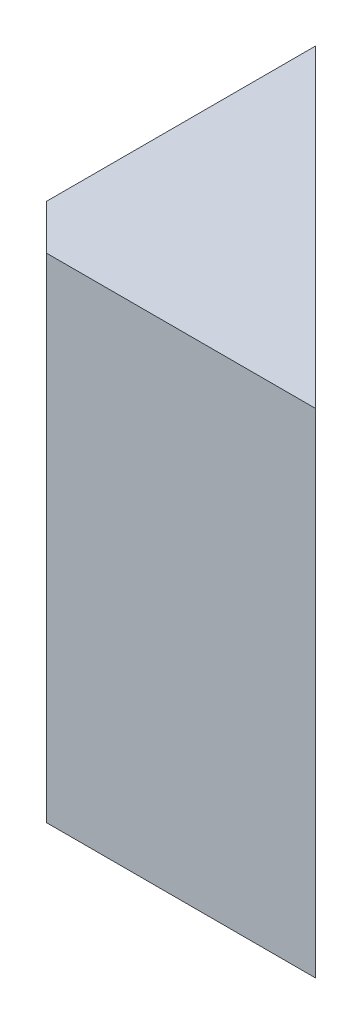
SolidWorks part; units mm, degrees
ref_plane "Front Plane" through (0, 0, 0) normal (0, 0, 1) x (1, 0, 0)
ref_plane "Top Plane" through (0, 0, 0) normal (0, 1, 0) x (1, 0, 0)
ref_plane "Right Plane" through (0, 0, 0) normal (1, 0, 0) x (0, 0, -1)
sketch "Sketch1" plane through (0, 0, 0) normal (0, 1, 0) x (1, 0, 0)
  line L0 (0, 0) -> (0, 0.3)
  line L1 (0, 0.15) -> (0.2, 0.15) construction
  line L2 (0.05, -0.05) -> (0.35, -0.05)
  line L3 (0, 0.3) -> (0.35, -0.05)
  line L4 (0, 0) -> (0.05, -0.05)
  circle A0 centre (0.2, 0.15) radius 0.2 construction
  point P8 (0.2, -0.05)
  dimension "D1" = 0.3
  dimension "D2" = 0.2
  dimension "D3" = 0.3
  dimension "D4" = 90
extrude "Boss-Extrude1" add sketch "Sketch1" along normal blind 0.55
equation "\"t\"= 0.3'thickness of the sheets"
equation "\"FlexJoint\"= 0.15'Width of flextures"
equation "\"FoldJoint\"= 0.4'Width of folding joints"
equation "\"AssembleAngle\"= 90'Angle of assembly parts"
equation "\"D1@Sketch1\"=\"t\""
equation "\"D2@Sketch1\"=\"FoldJoint\"/2"
equation "\"D3@Sketch1\"=\"t\""
equation "\"D4@Sketch1\"=\"AssembleAngle\""
